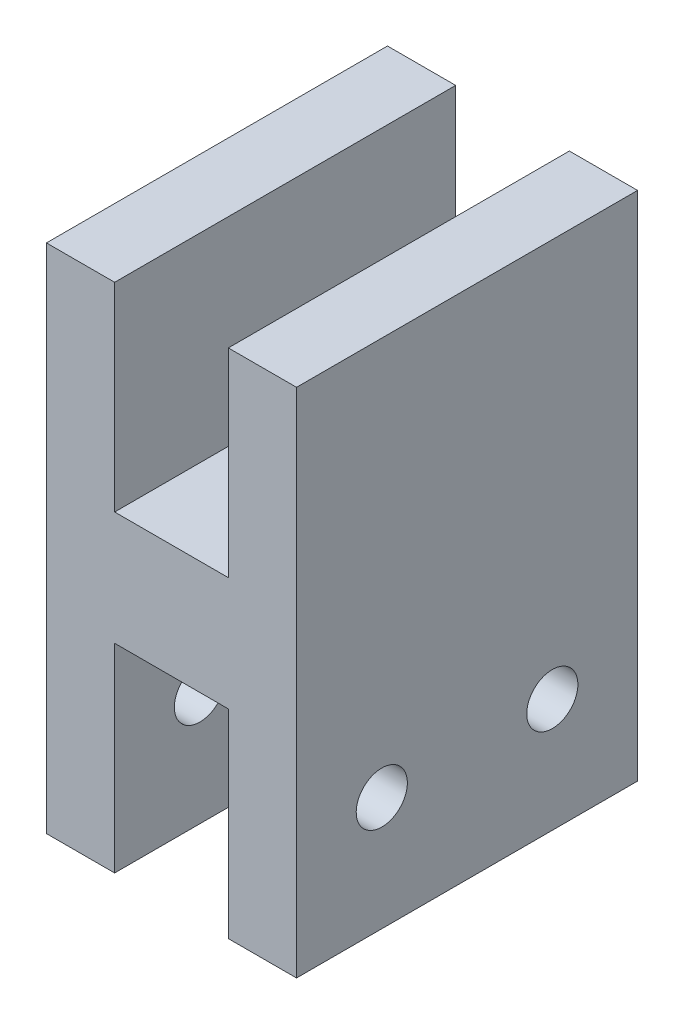
SolidWorks part; units mm, degrees
material "ABS"
ref_plane "Piano frontale" through (0, 0, 0) normal (0, 0, 1) x (1, 0, 0)
ref_plane "Piano superiore" through (0, 0, 0) normal (0, 1, 0) x (1, 0, 0)
ref_plane "Piano destro" through (0, 0, 0) normal (1, 0, 0) x (0, 0, -1)
sketch "Schizzo1" plane through (0, 0, 0) normal (0, 0, 1) x (1, 0, 0)
  line L0 (11, -27.5) -> (11, 17.5)
  line L1 (11, -27.5) -> (5, -27.5)
  line L2 (5, -27.5) -> (5, -10)
  line L3 (5, -10) -> (-5, -10)
  line L4 (-5, -10) -> (-5, -27.5)
  line L5 (-5, -27.5) -> (-11, -27.5)
  line L6 (-11, -27.5) -> (-11, 17.5)
  line L7 (11, 17.5) -> (5, 17.5)
  line L8 (5, 17.5) -> (5, 0)
  line L9 (5, 0) -> (-5, 0)
  line L10 (-5, 0) -> (-5, 17.5)
  line L11 (-5, 17.5) -> (-11, 17.5)
  dimension "D1" = 10
  dimension "D2" = 10
  dimension "D3" = 6
  dimension "D4" = 45
  dimension "D5" = 17.5
extrude "Estrusione-Estrusione1" add sketch "Schizzo1" along normal blind 30
hole_wizard "Foro per Vite M4-1" positions "Schizzo3D1" profile "Schizzo3" hole size "M4" standard "ISO"
sketch3d "Schizzo3D1"
  line L0 (-11, -27.5, 15) -> (-11, -17.5, 15) construction
  line L1 (-11, -27.5, 30) -> (-11, -27.5, 0) construction
  line L2 (-11, -17.5, 15) -> (-11, -17.5, 7.5) construction
  line L4 (-11, -17.5, 15) -> (-11, -17.5, 22.5) construction
  point P17 (-11, -17.5, 7.5)
  point P19 (-11, -17.5, 22.5)
  dimension "D1" = 10
  dimension "D2" = 15
sketch "Schizzo3" plane through (-11, -17.5, 22.5) normal (0, 1, 0) x (0, 0, 1)
  line L0 (0, 0) -> (0, 31.3519)
  line L1 (0, 31.3519) -> (2.25, 30)
  line L2 (2.25, 30) -> (2.25, 0)
  line L5 (2.25, 0) -> (0, 0)
  line L10 (0, 31.3519) -> (-2.25, 30) construction
  line L11 (0, -6.35) -> (0, 107.95) construction
  dimension "Hole Dia." = 4.5
  dimension "Hole Depth" = 30
  dimension "Drill Angle" = 118
